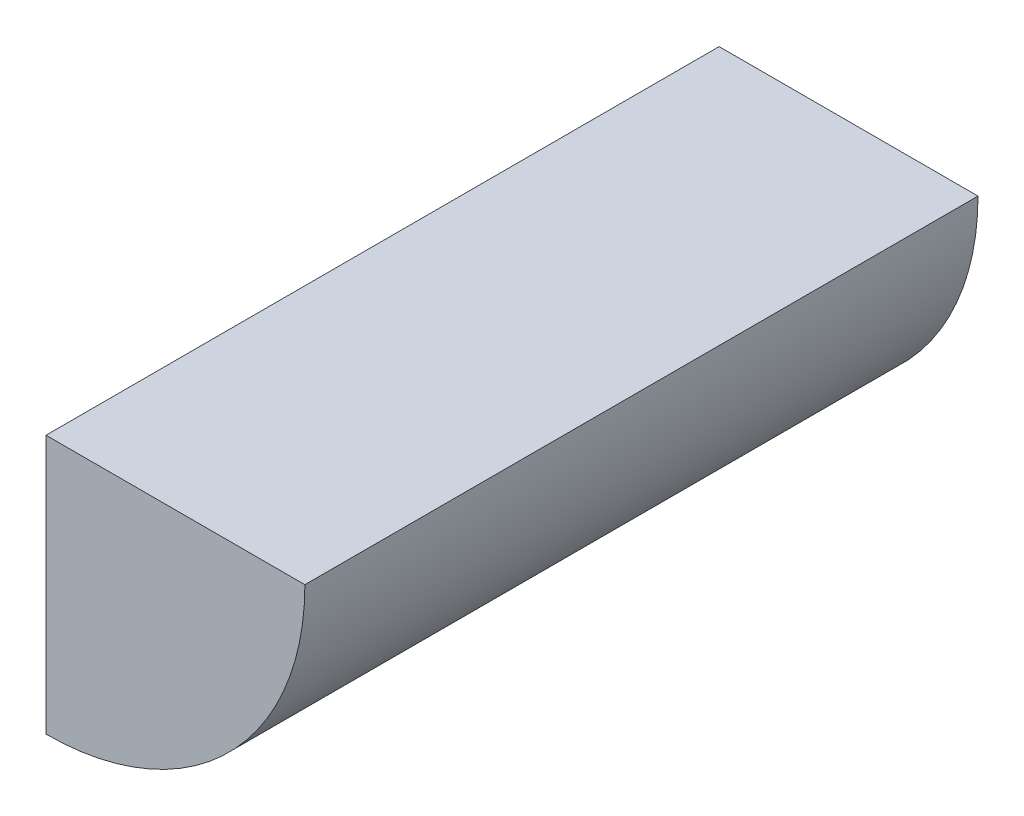
SolidWorks part; units mm, degrees
ref_plane "Front Plane" through (0, 0, 0) normal (0, 0, 1) x (1, 0, 0)
ref_plane "Top Plane" through (0, 0, 0) normal (0, 1, 0) x (1, 0, 0)
ref_plane "Right Plane" through (0, 0, 0) normal (1, 0, 0) x (0, 0, -1)
sketch "Sketch1" plane through (0, 0, 0) normal (0, 0, 1) x (1, 0, 0)
  line L0 (0, 19.9591) -> (0, -5.0409)
  line L1 (0, 19.9591) -> (25, 19.9591)
  arc A1 (25, 19.9591) -> (0, -5.0409) centre (0, 19.9591) cw
extrude "Boss-Extrude1" add sketch "Sketch1" along normal blind 65
